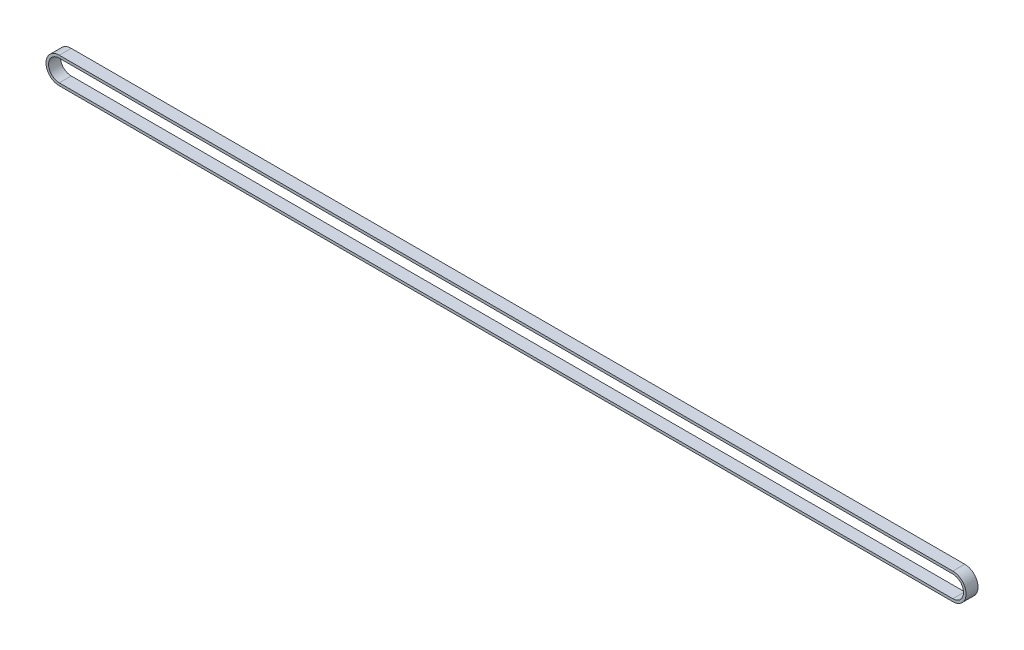
SolidWorks part; units mm, degrees
ref_plane "Front Plane" through (0, 0, 0) normal (0, 0, 1) x (1, 0, 0)
ref_plane "Top Plane" through (0, 0, 0) normal (0, 1, 0) x (1, 0, 0)
ref_plane "Right Plane" through (0, 0, 0) normal (1, 0, 0) x (0, 0, -1)
ref_plane "Plane1" through (0, 0, 772.6217) normal (0, 0, 1) x (1, 0, 0)
sketch "Sketch1" plane through (0, 0, 772.6217) normal (0, 0, 1) x (1, 0, 0)
  line L0 (505.5069, -30.5281) -> (131.5069, -30.5281)
  line L1 (131.5069, -21.5808) -> (505.5069, -21.5808)
  line L2 (131.5069, -31.6018) -> (505.5069, -31.6018)
  line L3 (505.5069, -20.5071) -> (131.5069, -20.5071)
  arc A0 (131.5069, -30.5281) -> (131.5069, -21.5808) centre (131.5069, -26.0545) cw
  arc A1 (505.5069, -21.5808) -> (505.5069, -30.5281) centre (505.5069, -26.0545) cw
  arc A2 (131.5069, -20.5071) -> (131.5069, -31.6018) centre (131.5069, -26.0545) ccw
  arc A3 (505.5069, -31.6018) -> (505.5069, -20.5071) centre (505.5069, -26.0545) ccw
  dimension "D1" = 374
extrude "Boss-Extrude1" add sketch "Sketch1" against normal blind 5
